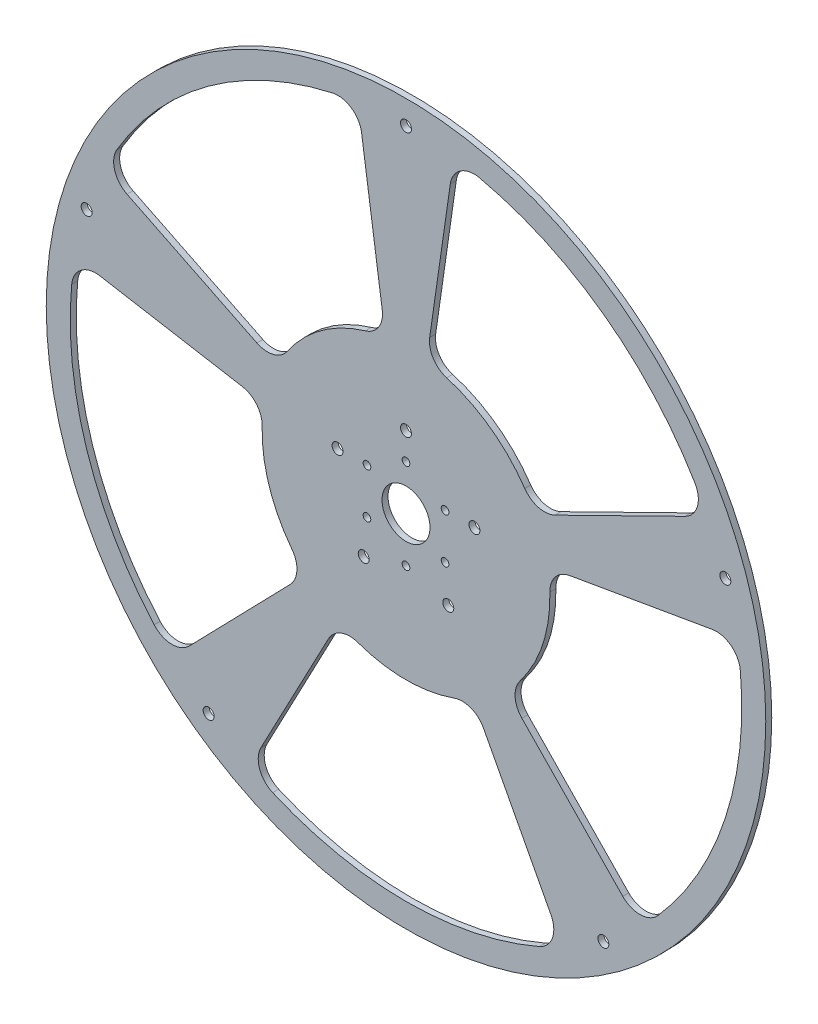
SolidWorks part; units mm, degrees
ref_plane "Front Plane" through (0, 0, 0) normal (0, 0, 1) x (1, 0, 0)
ref_plane "Top Plane" through (0, 0, 0) normal (0, 1, 0) x (1, 0, 0)
ref_plane "Right Plane" through (0, 0, 0) normal (1, 0, 0) x (0, 0, -1)
sketch "Sketch1" plane through (0, 0, 0) normal (0, 0, 1) x (1, 0, 0)
  line L0 (0, 177.8) -> (0, 0) construction
  line L1 (0, 0) -> (169.0978, 54.9432) construction
  line L2 (-169.0978, 54.9432) -> (0, 0) construction
  line L3 (0, 0) -> (-104.5082, -143.8432) construction
  line L4 (0, 0) -> (104.5082, -143.8432) construction
  line L5 (25.3351, 175.9857) -> (10.8579, 75.4224)
  line L6 (-25.4, 175.9764) -> (-10.8857, 75.4184)
  line L7 (68.3757, 33.6333) -> (159.5434, 78.4777)
  line L8 (75.0863, 12.9803) -> (175.2013, 30.2874)
  line L9 (53.1164, -54.6359) -> (123.9384, -127.4838)
  line L10 (35.548, -67.4002) -> (82.9453, -157.267)
  line L11 (-159.5434, 78.4777) -> (-68.3757, 33.6333)
  line L12 (-175.2013, 30.2874) -> (-75.0863, 12.9803)
  line L13 (-82.9453, -157.267) -> (-35.548, -67.4002)
  line L14 (-123.9384, -127.4838) -> (-53.1164, -54.6359)
  line L15 (0, 0) -> (-8.0097, 4.6244) construction
  line L16 (-8.0097, 4.6244) -> (-8.0097, -4.6244) construction
  line L17 (-8.0097, -4.6244) -> (0, -9.2488) construction
  line L18 (0, -9.2488) -> (8.0097, -4.6244) construction
  line L19 (8.0097, -4.6244) -> (8.0097, 4.6244) construction
  line L20 (8.0097, 4.6244) -> (0, 9.2488) construction
  line L21 (0, 9.2488) -> (-8.0097, 4.6244) construction
  line L22 (-8.0097, 4.6244) -> (-20.6772, 11.938) construction
  line L23 (0, 0) -> (0, 9.2488) construction
  line L24 (0, 9.2488) -> (0, 23.876) construction
  line L25 (0, 0) -> (8.0097, 4.6244) construction
  line L26 (8.0097, 4.6244) -> (20.6772, 11.938) construction
  line L27 (0, 0) -> (8.0097, -4.6244) construction
  line L28 (8.0097, -4.6244) -> (20.6772, -11.938) construction
  line L29 (0, 0) -> (0, -9.2488) construction
  line L30 (0, -9.2488) -> (0, -23.876) construction
  line L31 (0, 0) -> (-8.0097, -4.6244) construction
  line L32 (-8.0097, -4.6244) -> (-20.6772, -11.938) construction
  circle A0 centre (0, 0) radius 190.5
  arc A1 (-10.8857, 75.4184) -> (-68.3757, 33.6333) centre (0, 0) ccw
  arc A2 (-25.4, 175.9764) -> (-159.5434, 78.4777) centre (0, 0) ccw
  arc A3 (68.3757, 33.6333) -> (10.8579, 75.4224) centre (0, 0) ccw
  arc A4 (-75.0863, 12.9803) -> (-53.1164, -54.6359) centre (0, 0) ccw
  arc A5 (53.1164, -54.6359) -> (75.0863, 12.9803) centre (0, 0) ccw
  arc A6 (-35.548, -67.4002) -> (35.548, -67.4002) centre (0, 0) ccw
  arc A7 (159.5434, 78.4777) -> (25.3351, 175.9857) centre (0, 0) ccw
  arc A8 (123.9384, -127.4838) -> (175.2013, 30.2874) centre (0, 0) ccw
  arc A9 (-82.9453, -157.267) -> (82.9453, -157.267) centre (0, 0) ccw
  arc A10 (-175.2013, 30.2874) -> (-123.9384, -127.4838) centre (0, 0) ccw
  circle A11 centre (0, 0) radius 76.2 construction
  circle A12 centre (0, 0) radius 177.8 construction
  circle A13 centre (0, 0) radius 12.7
  circle A14 centre (-36.2353, 11.7735) radius 2.9
  circle A15 centre (-22.3946, -30.8235) radius 2.9
  circle A16 centre (22.3946, -30.8235) radius 2.9
  circle A17 centre (36.2353, 11.7735) radius 2.9
  circle A18 centre (0, 38.1) radius 2.9
  circle A19 centre (-169.0978, 54.9432) radius 2.9
  circle A20 centre (0, 177.8) radius 2.9
  circle A21 centre (169.0978, 54.9432) radius 2.9
  circle A22 centre (104.5082, -143.8432) radius 2.9
  circle A23 centre (-104.5082, -143.8432) radius 2.9
  circle A24 centre (0, 0) radius 8.0097 construction
  circle A25 centre (-20.6772, 11.938) radius 2.032
  circle A26 centre (0, 23.876) radius 2.032
  circle A27 centre (20.6772, 11.938) radius 2.032
  circle A28 centre (20.6772, -11.938) radius 2.032
  circle A29 centre (0, -23.876) radius 2.032
  circle A30 centre (-20.6772, -11.938) radius 2.032
  point P55 (0, 0)
  point P57 (0, 0)
  point P60 (0, 0)
  point P77 (0, 0)
  dimension "D1" = 381
  dimension "D2" = 152.4
  dimension "D3" = 355.6
  dimension "D22" = 25.4
  dimension "D23" = 5.8
  dimension "D24" = 5.8
  dimension "D25" = 5.8
  dimension "D26" = 5.8
  dimension "D27" = 5.8
  dimension "D33" = 5.8
  dimension "D36" = 4.064
  dimension "D4" = 72
  dimension "D5" = 72
  dimension "D6" = 72
  dimension "D7" = 72
  dimension "D8" = 25.4
  dimension "D9" = 25.4
  dimension "D10" = 25.4
  dimension "D11" = 25.4
  dimension "D12" = 25.4
  dimension "D13" = 25.4
  dimension "D14" = 25.4
  dimension "D15" = 25.4
  dimension "D16" = 25.4
  dimension "D17" = 25.4
  dimension "D18" = 21.7158
  dimension "D19" = 50.6702
  dimension "D20" = 50.6702
  dimension "D21" = 50.7351
  dimension "D28" = 38.1
  dimension "D29" = 38.1
  dimension "D30" = 38.1
  dimension "D31" = 38.1
  dimension "D32" = 38.1
  dimension "D35" = 23.876
  dimension "D34" = 5
  dimension "D37" = 6
extrude "Boss-Extrude3" add sketch "Sketch1" along normal blind 3.175
fillet "Fillet1" radius 12.7 1 edges at (-175.2013, 30.2874, 1.5875)
fillet "Fillet2" radius 12.7 13 edges at (35.548, -67.4002, 1.5875) (123.9384, -127.4838, 1.5875) (53.1164, -54.6359, 1.5875) (75.0863, 12.9803, 1.5875) (175.2013, 30.2874, 1.5875) (68.3757, 33.6333, 1.5875) (159.5434, 78.4777, 1.5875) (25.3351, 175.9857, 1.5875) (10.8579, 75.4224, 1.5875) (-10.8857, 75.4184, 1.5875) (-68.3757, 33.6333, 1.5875) (-25.4, 175.9764, 1.5875) (-159.5434, 78.4777, 1.5875)
fillet "Fillet3" radius 12.7 6 edges at (-75.0863, 12.9803, 1.5875) (-123.9384, -127.4838, 1.5875) (-53.1164, -54.6359, 1.5875) (82.9453, -157.267, 1.5875) (-82.9453, -157.267, 1.5875) (-35.548, -67.4002, 1.5875)
